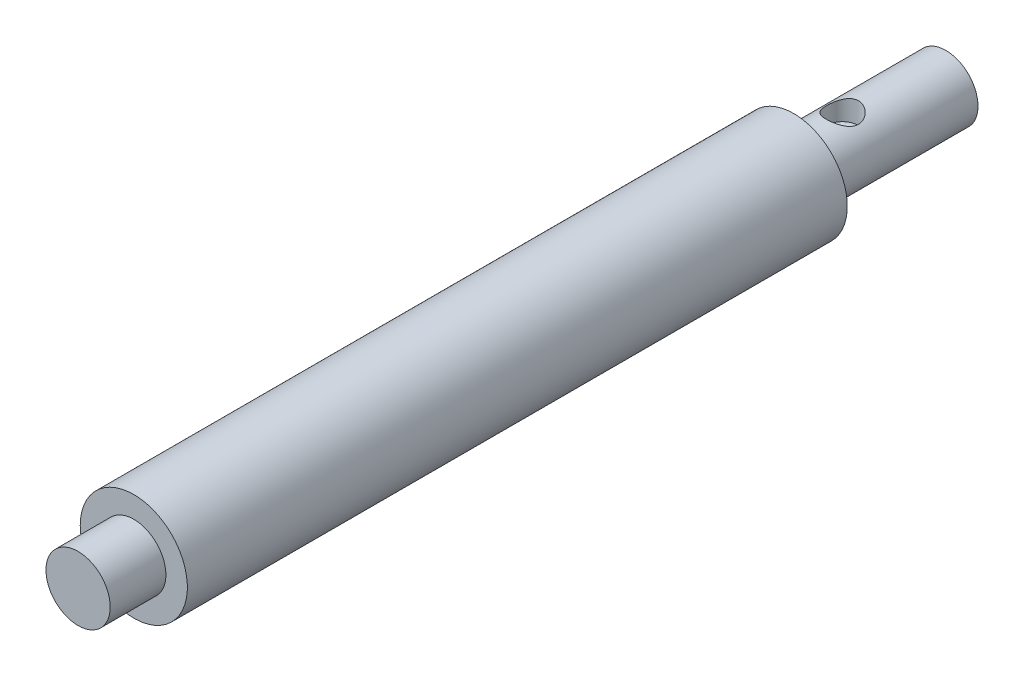
SolidWorks part; units mm, degrees
ref_plane "Front" through (0, 0, 0) normal (0, 0, 1) x (1, 0, 0)
ref_plane "Top" through (0, 0, 0) normal (0, 1, 0) x (1, 0, 0)
ref_plane "Right" through (0, 0, 0) normal (1, 0, 0) x (0, 0, -1)
sketch "Sketch1" plane through (0, 0, 0) normal (0, 0, 1) x (1, 0, 0)
  circle A0 centre (0, 0) radius 5
  dimension "D1" = 10
extrude "Extrude1" add sketch "Sketch1" along normal blind 61.6
sketch "Sketch2" plane through (0, 0, 61.6) normal (0, 0, 1) x (1, 0, 0)
  circle A0 centre (0, 0) radius 3
  dimension "D1" = 6
extrude "Extrude2" add sketch "Sketch2" along normal blind 5.2
sketch "Sketch3" plane through (0, 0, 0) normal (0, 0, -1) x (-1, 0, 0)
  circle A0 centre (0, 0) radius 3
  dimension "D1" = 6
extrude "Extrude3" add sketch "Sketch3" along normal blind 14.2
ref_plane "Plane1" through (0, 3, 0) normal (0, 1, 0) x (-1, 0, 0)
sketch "Sketch5" plane through (0, 3, 0) normal (0, 1, 0) x (-1, 0, 0)
  circle A0 centre (0, -4.55) radius 1.5
  dimension "D1" = 3
  dimension "D2" = 4.55
extrude "Extrude5" cut sketch "Sketch5" against normal blind 2
